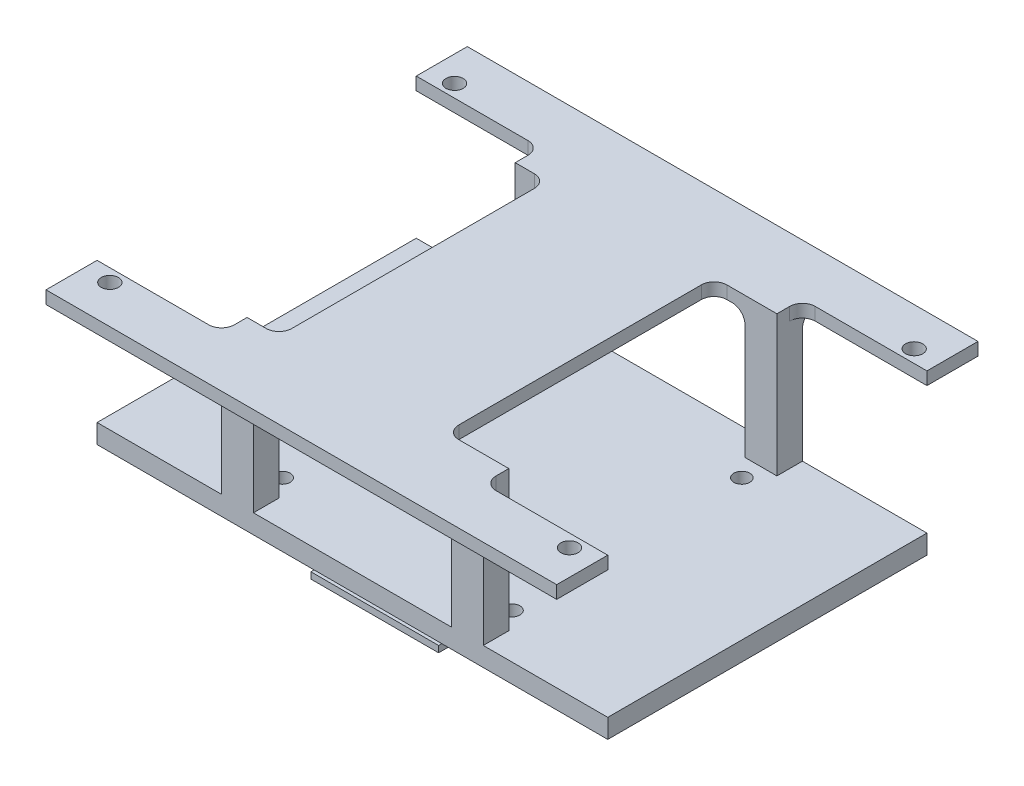
SolidWorks part; units mm, degrees
ref_plane "Front Plane" through (0, 0, 0) normal (0, 0, 1) x (1, 0, 0)
ref_plane "Top Plane" through (0, 0, 0) normal (0, 1, 0) x (1, 0, 0)
ref_plane "Right Plane" through (0, 0, 0) normal (1, 0, 0) x (0, 0, -1)
sketch "Sketch1" plane through (0, 0, 0) normal (0, 1, 0) x (1, 0, 0)
  line L1 (0, 0) -> (80, 0)
  line L2 (0, 0) -> (0, 50)
  line L3 (0, 50) -> (80, 50)
  line L4 (80, 0) -> (80, 50)
  dimension "D1" = 50
  dimension "D2" = 80
extrude "Boss-Extrude1" add sketch "Sketch1" along normal blind 3
sketch "Sketch2" plane through (0, 3, 0) normal (0, 1, 0) x (1, 0, 0)
  line L1 (0, 50) -> (80, 50) construction
  line L2 (0, 0) -> (80, 0) construction
  line L4 (0, 0) -> (0, 50) construction
  line L6 (80, 0) -> (80, 50) construction
  line L12 (22, 43) -> (22, 7) construction
  line L13 (22, 7) -> (58, 7) construction
  line L14 (58, 7) -> (58, 43) construction
  line L15 (58, 43) -> (22, 43) construction
  circle A0 centre (22, 43) radius 1.25
  circle A1 centre (58, 43) radius 1.25
  circle A2 centre (22, 7) radius 1.25
  circle A3 centre (58, 7) radius 1.25
  dimension "D5" = 2.5
  dimension "D6" = 2.5
  dimension "D7" = 2.5
  dimension "D8" = 2.5
  dimension "D2" = 7
  dimension "D1" = 7
  dimension "D3" = 22
  dimension "D4" = 22
extrude "Cut-Extrude1" cut sketch "Sketch2" against normal blind 3
sketch "Sketch3" plane through (0, 3, 0) normal (0, 1, 0) x (1, 0, 0)
  line L0 (19.5, 4) -> (19.5, 0)
  line L1 (0, 0) -> (80, 0) construction
  line L2 (19.5, 0) -> (24.5, 0)
  line L3 (24.5, 0) -> (24.5, 4)
  line L4 (19.5, 46) -> (19.5, 50)
  line L5 (0, 50) -> (80, 50) construction
  line L6 (19.5, 50) -> (24.5, 50)
  line L7 (24.5, 50) -> (24.5, 46)
  line L8 (55.5, 46) -> (55.5, 50)
  line L9 (55.5, 50) -> (60.5, 50)
  line L10 (60.5, 50) -> (60.5, 46)
  line L11 (55.5, 4) -> (55.5, 0)
  line L12 (55.5, 0) -> (60.5, 0)
  line L13 (60.5, 0) -> (60.5, 4)
  line L14 (19.5, 46) -> (24.5, 46)
  line L15 (55.5, 46) -> (60.5, 46)
  line L16 (19.5, 4) -> (24.5, 4)
  line L17 (55.5, 4) -> (60.5, 4)
  line L18 (22, 46) -> (22, 45.5) construction
  line L19 (22, 4.5) -> (22, 4) construction
  circle A0 centre (22, 7) radius 2.5
  circle A1 centre (22, 43) radius 2.5
  circle A2 centre (58, 43) radius 2.5
  circle A3 centre (58, 7) radius 2.5
  line M8 (0, 0) -> (80, 0)
  line M10 (80, 50) -> (0, 50)
  dimension "D1" = 5
  dimension "D2" = 0.5
  dimension "D3" = 0.5
extrude "Boss-Extrude2" add sketch "Sketch3" along normal blind 22 contours A0 L0 L3 M8 | A3 L11 L13 M8 | A2 L10 L8 M10 | A1 L7 L4 M10
ref_plane "Plane1" through (0, 23, 0) normal (0, 1, 0) x (1, 0, 0)
sketch "Sketch5" plane through (0, 23, 0) normal (0, 1, 0) x (1, 0, 0)
  line L0 (24.5, 50) -> (55.5, 50)
  line L1 (24.5, 46) -> (24.5, 4)
  line L2 (24.5, 0) -> (55.5, 0)
  line L3 (55.5, 46) -> (52.6609, 46)
  line L4 (55.5, 0) -> (55.5, 4)
  line L5 (55.5, 4) -> (55.5, 0) construction
  line L6 (55.5, 4) -> (52.6609, 4)
  line L7 (50.6609, 6) -> (50.6609, 44)
  line L8 (24.5, 0) -> (24.5, 4) construction
  line L9 (55.5, 46) -> (55.5, 50) construction
  line L10 (24.5, 50) -> (24.5, 46) construction
  line L11 (24.5, 0) -> (24.5, 4)
  line L12 (55.5, 46) -> (55.5, 50)
  line L13 (24.5, 50) -> (24.5, 46)
  arc A0 (52.6609, 4) -> (50.6609, 6) centre (52.6609, 6) cw
  arc A1 (52.6609, 46) -> (50.6609, 44) centre (52.6609, 44) ccw
  dimension "D1" = 2
extrude "Boss-Extrude3" add sketch "Sketch5" along normal blind 2
fillet "Fillet1" radius 2 2 edges at (24.5, 24, -4) (24.5, 24, -46)
sketch "Sketch8" plane through (0, 25, 0) normal (0, 1, 0) x (1, 0, 0)
  line L0 (0, 50) -> (80, 50)
  line L1 (0, 50) -> (0, 58)
  line L2 (80, 50) -> (80, 58)
  line L3 (0, 58) -> (80, 58)
  line L4 (0, 0) -> (80, 0)
  line L5 (0, 0) -> (0, -8)
  line L6 (80, 0) -> (80, -8)
  line L7 (0, -8) -> (80, -8)
  dimension "D1" = 8
  dimension "D2" = 8
extrude "Boss-Extrude4" add sketch "Sketch8" against normal blind 2
fillet "Fillet2" radius 2 4 edges at (60.5, 24, 0) (19.5, 24, 0) (60.5, 24, -50) (19.5, 24, -50)
sketch "Sketch6" plane through (0, 25, 0) normal (0, 1, 0) x (1, 0, 0)
  line L0 (40, 50) -> (40, 0) construction
  line L1 (4, 52) -> (76, 52) construction
  line L2 (4, 52) -> (4, -2) construction
  line L3 (4, -2) -> (76, -2) construction
  line L4 (76, 52) -> (76, -2) construction
  line L5 (0, 50) -> (80, 50) construction
  line L6 (0, 0) -> (80, 0) construction
  line L7 (40, 52) -> (40, -2) construction
  circle A0 centre (4, -2) radius 1.35
  circle A1 centre (4, 52) radius 1.35
  circle A2 centre (76, 52) radius 1.35
  circle A3 centre (76, -2) radius 1.35
  point P12 (40, 25)
  point P13 (40, 25)
  dimension "D3" = 2.7
  dimension "D1" = 54
  dimension "D2" = 72
extrude "Cut-Extrude2" cut sketch "Sketch6" against normal blind 2
sketch "Sketch12" plane through (0, 0, 0) normal (0, -1, 0) x (1, 0, 0)
  line L0 (40, 0) -> (40, -50) construction
  line L1 (0, 0) -> (80, 0) construction
  line L2 (0, -50) -> (80, -50) construction
  line L4 (30, -16.5) -> (30, -13.5)
  line L5 (30, -13.5) -> (50, -13.5)
  line L6 (50, -13.5) -> (50, -16.5)
  line L8 (0, -25) -> (80, -25) construction
  line L9 (0, 0) -> (0, -50) construction
  line L10 (80, 0) -> (80, -50) construction
  line L11 (30, -16.5) -> (50, -16.5)
  line L12 (30, -33.5) -> (30, -36.5)
  line L13 (30, -36.5) -> (50, -36.5)
  line L14 (50, -36.5) -> (50, -33.5)
  line L15 (30, -33.5) -> (50, -33.5)
  circle A0 centre (40, -25) radius 8.5 construction
  point P19 (40, -13.5)
  dimension "D1" = 17
  dimension "D2" = 3
  dimension "D3" = 20
extrude "Boss-Extrude6" add sketch "Sketch12" along normal blind 5
sketch "Sketch13" plane through (0, 0, -13.5) normal (0, 0, 1) x (1, 0, 0)
  line L0 (30, -5) -> (30, -4)
  line L1 (30, -5) -> (30, 0) construction
  line L2 (30, -4) -> (50, -4)
  line L3 (50, -5) -> (50, 0) construction
  line L4 (50, -4) -> (50, -5)
  line L5 (50, -5) -> (30, -5)
  dimension "D1" = 1
extrude "Boss-Extrude7" add sketch "Sketch13" along normal blind 10
sketch "Sketch14" plane through (0, -4, 0) normal (0, 1, 0) x (1, 0, 0)
  line L0 (40, 3.5) -> (40, 16.5) construction
  line L1 (30, 3.5) -> (50, 3.5) construction
  line L2 (30, 16.5) -> (50, 16.5) construction
  circle A0 centre (40, 10) radius 1.5
  dimension "D1" = 3
extrude "Cut-Extrude5" cut sketch "Sketch14" against normal up to surface (1 mm away) up to face at (40, -5, -10)
sketch "Sketch15" plane through (0, 0, 0) normal (-1, 0, 0) x (0, 0, 1)
  line L0 (-25, 25) -> (-25, 0) construction
  line L1 (-44, 25) -> (-6, 25) construction
  line L2 (0, 0) -> (-50, 0) construction
ref_plane "Plane2" through (0, 0, -25) normal (0, 0, -1) x (0, -1, 0)
mirror "Mirror1" about plane through (0, 0, -25) normal (0, 0, -1) of "Boss-Extrude7", "Cut-Extrude5"
fillet "Fillet3" radius 2 8 edges at (55.5, 23, -2) (24.5, 23, -2) (22, 23, -50) (24.5, 23, -48) (58, 23, -50) (55.5, 23, -48) (22, 23, 0) (58, 23, 0)
fillet "Fillet4" radius 2 6 edges at (30, 0, -35) (30, 0, -15) (40, 0, -36.5) (50, 0, -35) (50, 0, -15) (40, 0, -13.5)
